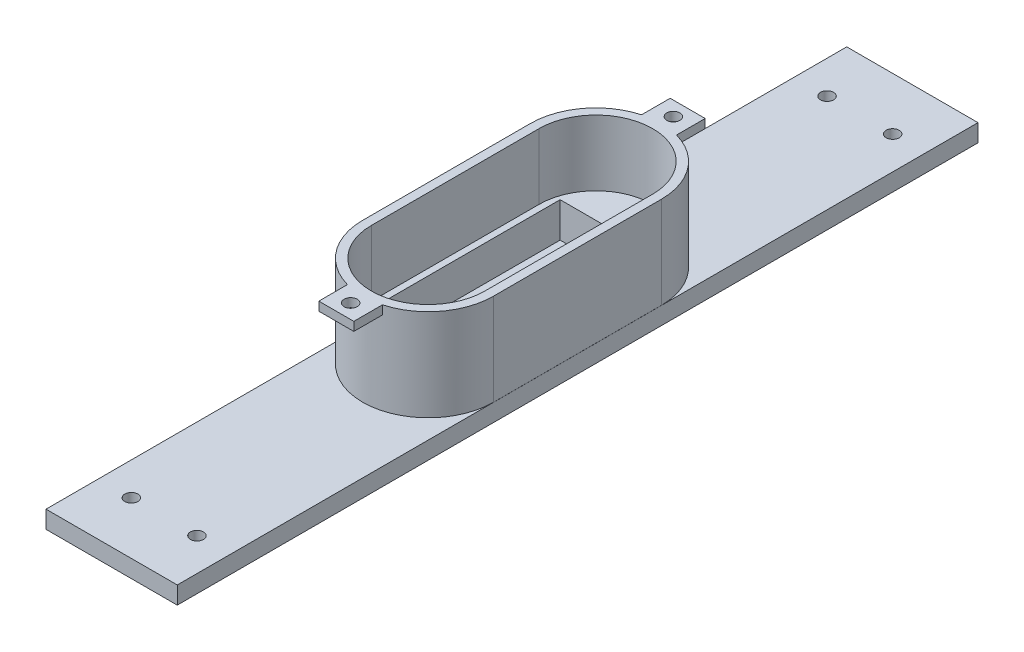
SolidWorks part; units mm, degrees
ref_plane "Plan de face" through (0, 0, 0) normal (0, 0, 1) x (1, 0, 0)
ref_plane "Plan de dessus" through (0, 0, 0) normal (0, 1, 0) x (1, 0, 0)
ref_plane "Plan de droite" through (0, 0, 0) normal (1, 0, 0) x (0, 0, -1)
sketch "Esquisse1" plane through (0, 0, 0) normal (1, 0, 0) x (0, 0, -1)
  line L1 (-116.205, 49.1687) -> (116.205, 49.1687)
  line L3 (0, 55) -> (0, -55) construction
  point P2 (0, 49.1687)
  dimension "D1" = 232.41
extrude "Extru.-Mince1" add sketch "Esquisse1" along normal mid plane 38.1 thin
sketch "Esquisse6" plane through (0, 49.1687, 0) normal (0, 1, 0) x (1, 0, 0)
  line L0 (0, 24.3459) -> (0, -24.3459) construction
  line L1 (16.4846, 24.3459) -> (16.4846, -24.3459)
  line L2 (-16.4846, 24.3459) -> (-16.4846, -24.3459)
  line L3 (15.9766, 23.8379) -> (15.9766, -23.8379) construction
  arc A0 (16.4846, 24.3459) -> (-16.4846, 24.3459) centre (0, 24.3459) ccw
  arc A1 (-16.4846, -24.3459) -> (16.4846, -24.3459) centre (0, -24.3459) ccw
  arc A2 (15.9766, 23.8379) -> (-15.9766, 23.8379) centre (0, 23.8379) ccw construction
  point P4 (0, 0)
  dimension "D1" = 0.508
  dimension "D2" = 0.508
extrude "Extru.-Mince2" add sketch "Esquisse6" along normal blind 26.67 thin thin type one direction wall 2.54
sketch "Esquisse13" plane through (0, 49.1687, 0) normal (0, 1, 0) x (1, 0, 0)
  line L0 (-16.4846, 24.3459) -> (-16.4846, -24.3459)
  line L1 (-16.4846, 24.3459) -> (-16.4846, -24.3459) construction
  line L2 (16.4846, -24.3459) -> (16.4846, 24.3459)
  arc A0 (-16.4846, -24.3459) -> (16.4846, -24.3459) centre (0, -24.3459) ccw construction
  arc A1 (-16.4846, -24.3459) -> (16.4846, -24.3459) centre (0, -24.3459) ccw
  arc A2 (16.4846, 24.3459) -> (-16.4846, 24.3459) centre (0, 24.3459) ccw
extrude "Boss.-Extru.2" add sketch "Esquisse13" along normal blind 7.62
sketch "Esquisse2" plane through (0, 56.7887, 0) normal (0, 1, 0) x (1, 0, 0)
  line L7 (-14.605, -28.575) -> (14.605, -28.575)
  line L8 (-14.605, -28.575) -> (-14.605, 28.575)
  line L9 (-14.605, 28.575) -> (14.605, 28.575)
  line L10 (14.605, -28.575) -> (14.605, 28.575)
  line L11 (-14.605, -28.575) -> (14.605, 28.575) construction
  line L12 (-14.605, 28.575) -> (14.605, -28.575) construction
  point P0 (0, 0)
  dimension "D1" = 29.21
  dimension "D2" = 57.15
extrude "Enlèv. mat.-Extru.1" cut sketch "Esquisse2" against normal blind 10.16
sketch "Esquisse7" plane through (0, 46.6287, 0) normal (0, 1, 0) x (1, 0, 0)
  line L0 (-9.525, 9.525) -> (-9.525, -9.525) construction
  line L1 (-9.525, -9.525) -> (9.525, -9.525) construction
  circle A0 centre (-9.525, 9.525) radius 1.65
  circle A1 centre (9.525, 9.525) radius 1.65
  circle A2 centre (9.525, -9.525) radius 1.65
  circle A3 centre (-9.525, -9.525) radius 1.65
  point P8 (0, -9.525)
  point P10 (-9.525, 0)
  dimension "D1" = 19.05
  dimension "D5" = 3.3
  dimension "D2" = 19.05
extrude "Enlèv. mat.-Extru.2" cut sketch "Esquisse7" against normal up to next
sketch "Esquisse8" plane through (0, 46.6287, 0) normal (0, 1, 0) x (1, 0, 0)
  circle A0 centre (0, 0) radius 10.16
  dimension "D1" = 20.32
extrude "Enlèv. mat.-Extru.3" cut sketch "Esquisse8" against normal through all
sketch "Esquisse9" plane through (0, 75.8387, 0) normal (0, 1, 0) x (1, 0, 0)
  line L0 (-5.08, 40.8305) -> (-5.08, 50.9905)
  line L1 (-5.08, 50.9905) -> (5.08, 50.9905)
  line L2 (5.08, 50.9905) -> (5.08, 40.8305)
  line L3 (5.08, 40.8305) -> (-5.08, 40.8305)
  line L4 (-19.05, 98.6847) -> (19.05, 98.6847) construction
  line L5 (-19.05, -116.205) -> (-19.05, 116.205) construction
  line L6 (19.05, -116.205) -> (19.05, 116.205) construction
  arc A0 (16.4846, 24.3459) -> (-16.4846, 24.3459) centre (0, 24.3459) ccw construction
  point P10 (0, 40.8305)
  point P11 (0, 98.6847)
  dimension "D1" = 10.16
  dimension "D2" = 10.16
extrude "Boss.-Extru.1" add sketch "Esquisse9" against normal blind 2.54
hole_wizard "Dégagement #61" positions "Esquisse10" profile "Esquisse11" hole size "#6" standard "Ansi Inch"
sketch "Esquisse10" plane through (0, 75.8387, 0) normal (0, 1, 0) x (1, 0, 0)
  line L0 (5.08, 42.6797) -> (5.08, 50.9905) construction
  point P0 (0, 46.8351)
  point P5 (5.08, 46.8351)
sketch "Esquisse11" plane through (0, 75.8387, -46.8351) normal (1, 0, 0) x (0, 0, 1)
  line L0 (0, 0) -> (0, 2.54)
  line L1 (0, 2.54) -> (1.8986, 2.54)
  line L2 (1.8986, 2.54) -> (1.8986, 0)
  line L5 (1.8986, 0) -> (0, 0)
  line L11 (0, -6.35) -> (0, 107.95) construction
  dimension "Diamètre du perçage jusqu'au prochain" = 3.7973
  dimension "Profondeur du perçage jusqu'au prochain" = 2.54
mirror "Symétrie1" about plane through (0, 0, 0) normal (0, 0, 1) of "Dégagement #61", "Boss.-Extru.1"
sketch "Esquisse12" plane through (0, 44.0887, 0) normal (0, 1, 0) x (1, 0, 0)
  line L0 (-5.08, -28.575) -> (-5.08, -109.855)
  line L1 (-14.605, -28.575) -> (14.605, -28.575) construction
  line L3 (-5.08, -109.855) -> (5.08, -109.855)
  line L4 (5.08, -109.855) -> (5.08, -28.575)
  line L5 (5.08, -28.575) -> (-5.08, -28.575)
  line L6 (5.08, -50.9905) -> (-5.08, -50.9905) construction
  point P6 (0, -50.9905)
  point P9 (0, -109.855)
  dimension "D1" = 81.28
  dimension "D2" = 10.16
extrude "Enlèv. mat.-Extru.4" cut sketch "Esquisse12" along normal blind 3.81
sketch "Esquisse14" plane through (0, 56.7887, 0) normal (0, 1, 0) x (1, 0, 0)
  line L0 (-5.08, -28.575) -> (5.08, -28.575)
  line L1 (5.08, -28.575) -> (5.08, -40.0282)
  line L2 (-5.08, -40.0282) -> (-5.08, -28.575)
  line L3 (-14.605, -28.575) -> (14.605, -28.575) construction
  arc A0 (-16.4846, -24.3459) -> (16.4846, -24.3459) centre (0, -24.3459) ccw construction
  arc A1 (-5.08, -40.0282) -> (5.08, -40.0282) centre (0, -24.3459) ccw
  dimension "D1" = 10.16
extrude "Enlèv. mat.-Extru.5" cut sketch "Esquisse14" against normal up to surface (8.89 mm away) up to face at (0, 47.8987, 69.215)
hole_wizard "Dégagement #62" positions "Esquisse15" profile "Esquisse16" hole size "#6" standard "Ansi Inch" end condition through all
sketch "Esquisse15" plane through (0, 49.1687, 0) normal (0, 1, 0) x (1, 0, 0)
  circle A0 centre (9.525, 100.965) radius 1.8986 construction
  circle A1 centre (-9.525, 100.965) radius 1.8986 construction
  circle A2 centre (9.525, -100.965) radius 1.8986 construction
  circle A3 centre (-9.525, -100.965) radius 1.8986 construction
  point P0 (-9.525, 100.965)
  point P2 (9.525, 100.965)
  point P9 (9.525, -100.965)
  point P11 (-9.525, -100.965)
  point P14 (0, 0)
  point P17 (0, 0)
sketch "Esquisse16" plane through (-9.525, 49.1687, -100.965) normal (1, 0, 0) x (0, 0, 1)
  line L0 (0, 0) -> (0, 5.08)
  line L1 (0, 5.08) -> (1.8986, 5.08)
  line L2 (1.8986, 5.08) -> (1.8986, 0)
  line L5 (1.8986, 0) -> (0, 0)
  line L11 (0, -6.35) -> (0, 107.95) construction
  dimension "Diamètre du perçage jusqu'au prochain" = 3.7973
  dimension "Profondeur du perçage jusqu'au prochain" = 5.08
